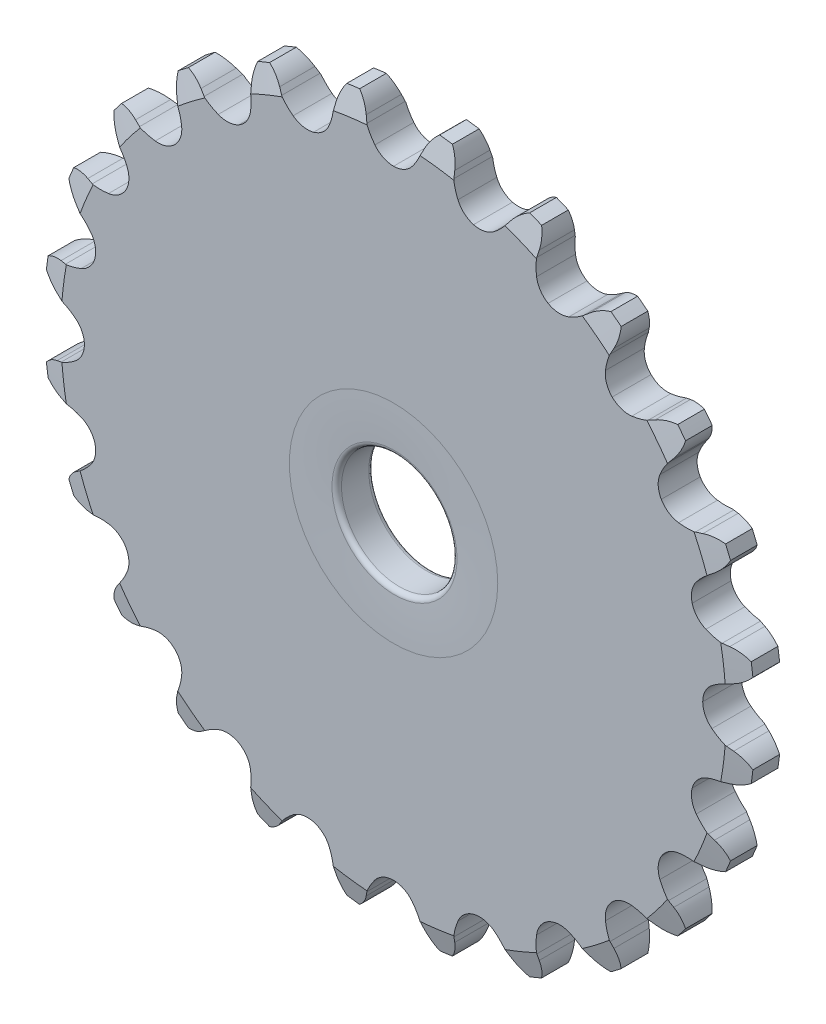
SolidWorks part; units mm, degrees
ref_plane "Front Plane" through (0, 0, 0) normal (0, 0, 1) x (1, 0, 0)
ref_plane "Top Plane" through (0, 0, 0) normal (0, 1, 0) x (1, 0, 0)
ref_plane "Right Plane" through (0, 0, 0) normal (1, 0, 0) x (0, 0, -1)
sketch "Sketch1" plane through (0, 0, 0) normal (0, 0, 1) x (1, 0, 0)
  line L0 (4.7625, 38.989) -> (-4.7625, 38.989) construction
  line L1 (-38.989, 0) -> (-33.909, 0) construction
  circle A0 centre (0, 0) radius 38.989
  circle A1 centre (0, 0) radius 6.35
  circle A3 centre (0, 0) radius 36.4869 construction
  point P6 (0, 38.989)
  point P8 (33.7655, 19.4945)
  point P9 (37.6605, 10.0911)
  point P10 (10.0911, 37.6605)
  point P11 (19.4945, 33.7655)
  point P12 (27.5694, 27.5694)
  point P13 (0, 0)
  point P14 (38.989, 0)
  point P15 (37.6605, -10.0911)
  point P16 (33.7655, -19.4945)
  point P17 (27.5694, -27.5694)
  point P18 (19.4945, -33.7655)
  point P19 (10.0911, -37.6605)
  point P20 (0, -38.989)
  point P21 (-10.0911, -37.6605)
  point P22 (-19.4945, -33.7655)
  point P23 (-27.5694, -27.5694)
  point P24 (-33.7655, -19.4945)
  point P25 (-37.6605, -10.0911)
  point P26 (-38.989, 0)
  point P27 (-37.6605, 10.0911)
  point P29 (-33.7655, 19.4945)
  point P30 (-27.5694, 27.5694)
  point P31 (-19.4945, 33.7655)
  point P32 (-10.0911, 37.6605)
  point P36 (0, 38.989)
  dimension "ID" = 12.7
  dimension "OD" = 77.978
  dimension "Pitch Diameter" = 72.9739
  dimension "Pitch" = 9.525
  dimension "Number of Teeth" = 24
sketch "Sketch2" plane through (0, 0, 0) normal (1, 0, 0) x (0, 0, -1)
  line L0 (-2.1336, 0) -> (2.1336, 0) construction
  line L1 (-2.1336, 38.989) -> (2.1336, 38.989) construction
  point P4 (0, 38.989)
  dimension "Overall Width" = 4.2672
sketch "Sketch3" plane through (0, 0, 0) normal (1, 0, 0) x (0, 0, -1)
  line L1 (-2.1336, 38.989) -> (2.1336, 38.989)
  line L2 (-2.1336, 38.989) -> (-2.1336, 11.43)
  line L3 (-1.4941, 6.35) -> (1.4941, 6.35)
  line L5 (-2.1336, 38.989) -> (2.1336, 38.989) construction
  line L7 (0, 38.989) -> (0, 6.35) construction
  line L10 (-2.1336, 0) -> (2.1336, 0) construction
  line L15 (2.1336, 38.989) -> (2.1336, 11.43)
  arc A0 (-2.1336, 11.43) -> (-2.0269, 6.8585) centre (95.8689, 11.43) ccw
  arc A1 (-2.0269, 6.8585) -> (-1.4941, 6.35) centre (-1.4941, 6.8834) ccw
  arc A2 (2.1336, 11.43) -> (2.0269, 6.8585) centre (-95.8689, 11.43) cw
  arc A3 (2.0269, 6.8585) -> (1.4941, 6.35) centre (1.4941, 6.8834) cw
  dimension "D2" = 0.5334
  dimension "D1" = 4.0538
  dimension "D3" = 22.86
revolve "Revolve1" add sketch "Sketch3" angle 360 about L0
sketch "Sketch4" plane through (0, 0, 0) normal (0, 0, 1) x (1, 0, 0)
  line L0 (0, 0) -> (0, 72.9739) construction
  line L1 (0, 0) -> (18.887, 70.4873) construction
  line L2 (-25.8002, 44.6872) -> (44.6872, 25.8002) construction
  line L3 (22.0014, 69.6529) -> (3.1143, -0.8345) construction
  line L4 (45.3275, 28.1899) -> (-25.1598, 47.0769) construction
  line L5 (13.1982, 36.7989) -> (0, 31.332) construction
  line L6 (13.1982, 36.7989) -> (0, 35.2173) construction
  line L7 (6.5906, 36.0071) -> (4.6623, 52.0986) construction
  line L8 (12.0761, 72.3123) -> (-6.8109, 1.825) construction
  line L9 (44.4469, 24.9035) -> (-26.0404, 43.7905) construction
  line L10 (0, 0) -> (9.525, 72.3496) construction
  line L11 (6.5906, 36.0071) -> (6.5117, 36.6656)
  line L12 (12.2959, 34.4784) -> (12.6935, 35.0092)
  line L13 (35.2437, -9.4435) -> (36.4869, 0) construction
  line L14 (38.6554, -5.0891) -> (0, 0) construction
  line L15 (37.6605, -10.0911) -> (0, 0) construction
  line L16 (0, 0) -> (38.989, 0) construction
  arc A0 (11.0137, 33.1973) -> (8.7759, 32.7522) centre (9.4364, 35.2792) cw
  circle A1 centre (9.4435, 35.2437) radius 2.5794 construction
  arc A2 (7.0605, 34.2566) -> (6.5906, 36.0071) centre (13.193, 36.8409) cw
  circle A3 centre (0, 0) radius 36.4869 construction
  circle A4 centre (2.3924, 36.172) radius 4.1488 construction
  arc A5 (5.1681, 39.2555) -> (6.5117, 36.6656) centre (2.3924, 36.172) cw
  arc A6 (7.0605, 34.2566) -> (8.7759, 32.7522) centre (9.4674, 35.2709) ccw
  arc A7 (11.0137, 33.1973) -> (12.2959, 34.4784) centre (6.995, 38.5017) ccw
  arc A8 (15.1521, 36.5803) -> (12.6935, 35.0092) centre (16.0141, 32.522) ccw
  arc A9 (5.1681, 39.2555) -> (15.1521, 36.5803) centre (8.7759, 32.7522) cw
  circle A10 centre (0, 0) radius 36.4869 construction
  arc A11 (37.6605, -10.0911) -> (38.989, 0) centre (0, 0) ccw construction
  circle A12 centre (0, 0) radius 38.989 construction
  circle A13 centre (0, 0) radius 38.989 construction
  point P0 (35.8653, -4.7218)
  point P3 (0, 36.4869)
  point P4 (6.5906, 36.0071)
  point P9 (9.4435, 35.2437)
  point P15 (12.5578, 34.4092)
  point P18 (10.0838, 37.6334)
  point P29 (9.2032, 34.347)
  point P32 (2.6326, 37.0686)
  point P49 (10.7008, 39.9358)
  point P55 (35.2437, -9.4435)
  point P59 (36.4869, 0)
  dimension "D12" = 9.525
  dimension "Pitch Drawing Note Angle" = 105
extrude "Cut-Extrude1" cut sketch "Sketch4" against normal through all both and the other way through all
pattern_circular "CirPattern1" count 24 over 360 about axis through (0, 0, 0) along (0, 0, 1) of "Cut-Extrude1"
sketch "Sketch5" plane through (0, 0, 2.1336) normal (0, 0, 1) x (1, 0, 0)
  circle A0 centre (0, 0) radius 36.4869
  circle A1 centre (0, 0) radius 36.4869 construction
extrude "Cut-Extrude2" cut sketch "Sketch5" against normal through all draft 75 flip side to cut
mirror "Mirror1" about plane through (0, 0, 0) normal (0, 0, 1) of "Cut-Extrude2"
equation "\"K\"= 180 / \"Number of Teeth@Sketch1\""
equation "\"PD\"= \"Pitch@Sketch1\" / SIN ( \"K\" )"
equation "\"A\"= 35 + 60 / \"Number of Teeth@Sketch1\""
equation "\"B\"= 18 - 56 / \"Number of Teeth@Sketch1\""
equation "\"M\"= ( .8 * \"Dr@Sketch1\" ) * COS ( \"A\" )"
equation "\"R\"= ( ( 1.0005 * \"Dr@Sketch1\" ) + 0.003 ) / 2"
equation "\"T\"= 0.8 * \"Dr@Sketch1\" * SIN ( \"A\" )"
equation "\"V\"= 1.4 * \"Dr@Sketch1\" * SIN ( \"K\" )"
equation "\"W\"= 1.4 * \"Dr@Sketch1\" * COS ( \"K\" )"
equation "\"D3@Sketch4\" = \"T\""
equation "\"D2@Sketch4\" = \"M\""
equation "\"D1@Sketch4\" = \"R\""
equation "\"E\"= ( 1.3025 * \"Dr@Sketch1\" ) + 0.0015"
equation "\"D7@Sketch4\" = \"PD\""
equation "\"D5@Sketch4\" = \"B\""
equation "\"D6@Sketch4\" = \"E\""
equation "\"D8@Sketch4\" = \"E\""
equation "\"D4@Sketch4\" = \"A\""
equation "\"D9@Sketch4\" = \"W\""
equation "\"D10@Sketch4\" = \"V\""
equation "\"D11@Sketch4\" = \"K\""
equation "\"D1@CirPattern1\" = \"Number of Teeth@Sketch1\""
equation "\"D12@Sketch4\" = \"Pitch@Sketch1\""
equation "\"Pitch Diameter@Sketch1\"=\"PD\""
equation "\"D1@Sketch3\"=\"Overall Width@Sketch2\"*.95"
equation "\"D2@Sketch3\"=\"Overall Width@Sketch2\"*.125"
equation "\"D3@Sketch3\"=\"ID@Sketch1\"*1.8"
equation "\"Pitch Drawing Note Angle@Sketch4\"=(Round(\"Number of Teeth@Sketch1\"*.25)+1)*\"K\"*2"
